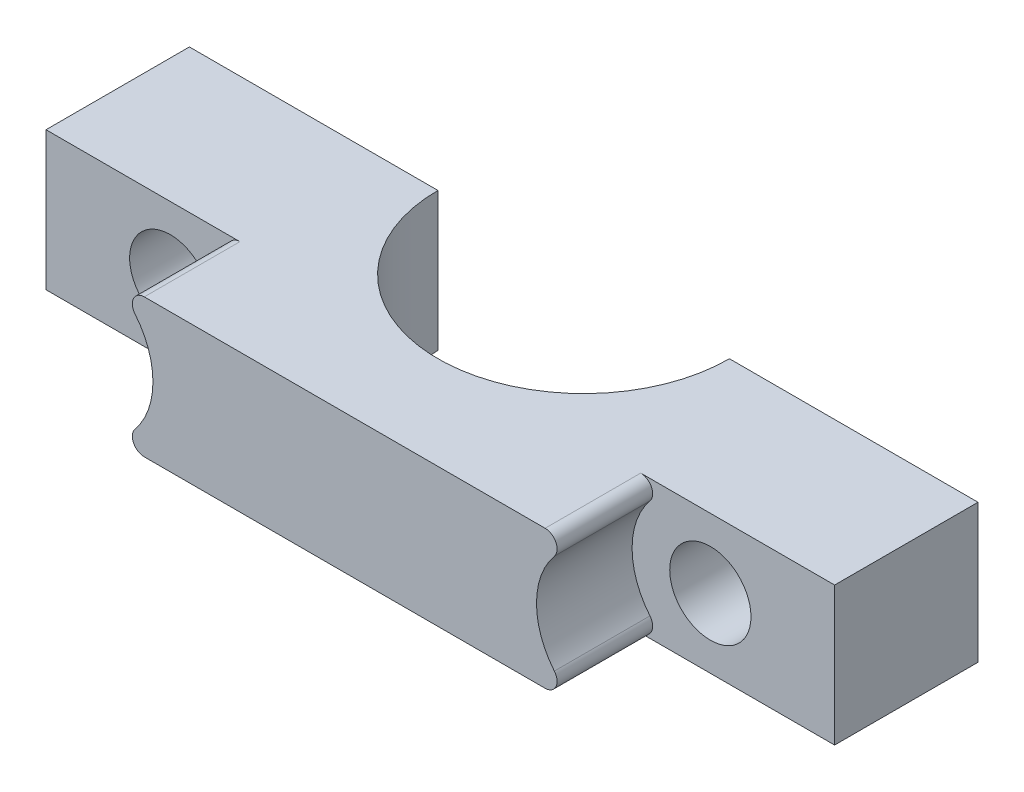
SolidWorks part; units mm, degrees
ref_plane "Front" through (0, 0, 0) normal (0, 0, 1) x (1, 0, 0)
ref_plane "Top" through (0, 0, 0) normal (0, 1, 0) x (1, 0, 0)
ref_plane "Right" through (0, 0, 0) normal (1, 0, 0) x (0, 0, -1)
sketch "Sketch1" plane through (0, 0, 0) normal (0, 1, 0) x (1, 0, 0)
  line L0 (-16.5, 0) -> (16.5, 0)
  line L1 (16.5, 0) -> (16.5, 10)
  line L2 (16.5, 10) -> (6.1, 10)
  line L3 (-6.1, 10) -> (-16.5, 10)
  line L4 (-16.5, 10) -> (-16.5, 0)
  line L5 (0, 18.1806) -> (0, -4.2196) construction
  arc A0 (6.1, 10) -> (-6.1, 10) centre (0, 10) cw
  dimension "D1" = 6.1
  dimension "D2" = 33
  dimension "D3" = 10
extrude "Boss-Extrude1" add sketch "Sketch1" along normal blind 5.8
hole_wizard "M3 Clearance Hole1" positions "Sketch3" profile "Sketch4" hole size "M3" standard "DIN" end condition through all
sketch "Sketch3" plane through (0, 0, 0) normal (0, 0, 1) x (1, 0, 0)
  line L0 (0, 10.9562) -> (0, -2.36) construction
  line L2 (-11.3, 8.16) -> (-11.3, -2.36) construction
  line L4 (-19.2001, 2.9) -> (41.8001, 2.9) construction
  point P0 (-11.3, 2.9)
  point P2 (11.3, 2.9)
sketch "Sketch4" plane through (-11.3, 2.9, 0) normal (1, 0, 0) x (0, -1, 0)
  line L0 (0, 0) -> (0, 10)
  line L1 (0, 10) -> (1.7, 10)
  line L2 (1.7, 10) -> (1.7, 0)
  line L5 (1.7, 0) -> (0, 0)
  line L11 (0, -6.35) -> (0, 107.95) construction
  dimension "Thru Hole Dia." = 3.4
  dimension "Thru Hole Depth" = 10
sketch "Sketch5" plane through (0, 0, 0) normal (0, 0, 1) x (1, 0, 0)
  line L0 (-9.7783, 5.8) -> (-16.5, 5.8)
  line L1 (-16.5, 5.8) -> (16.5, 5.8) construction
  line L2 (-16.5, 5.8) -> (-16.5, 0)
  line L3 (-16.5, 0) -> (-9.7783, 0)
  line L4 (-16.5, 0) -> (16.5, 0) construction
  line L5 (0, 8.4021) -> (0, -2.6012) construction
  line L6 (16.5, 0) -> (9.7783, 0)
  line L7 (16.5, 5.8) -> (16.5, 0)
  line L8 (9.7783, 5.8) -> (16.5, 5.8)
  arc A0 (-9.7783, 0) -> (-9.7783, 5.8) centre (-11.3, 2.9) ccw
  arc A1 (9.7783, 0) -> (9.7783, 5.8) centre (11.3, 2.9) cw
  dimension "D1" = 6.55
extrude "Cut-Extrude1" cut sketch "Sketch5" against normal blind 4
fillet "Fillet1" radius 0.5 4 edges at (9.7783, 0, -2) (9.7783, 5.8, -2) (-9.7783, 0, -2) (-9.7783, 5.8, -2)
